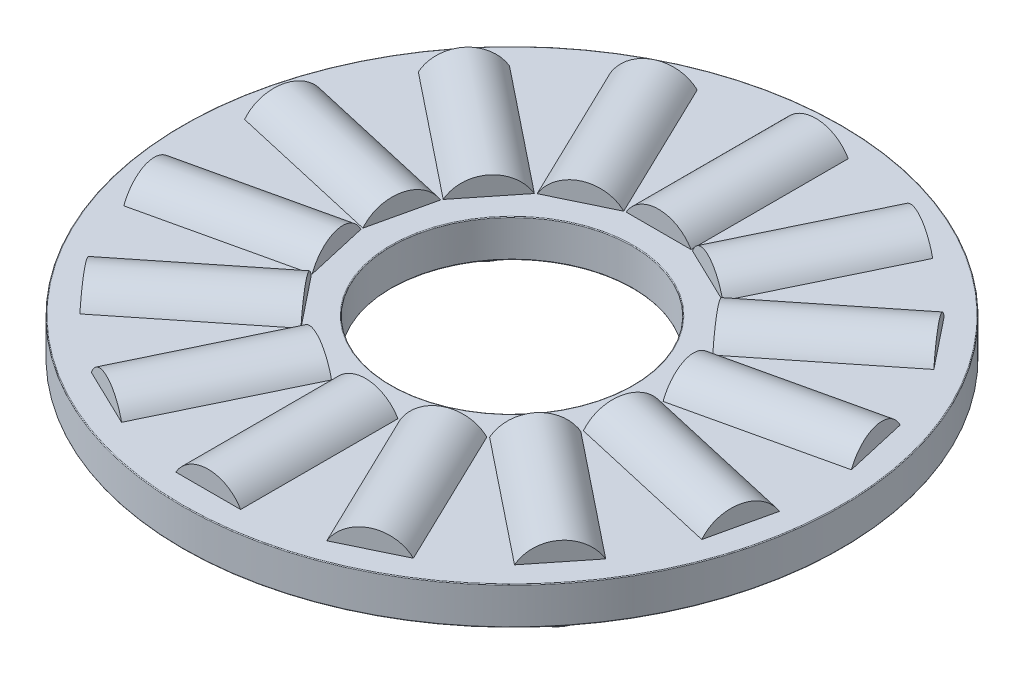
SolidWorks part; units mm, degrees
ref_plane "Front Plane" through (0, 0, 0) normal (0, 0, 1) x (1, 0, 0)
ref_plane "Top Plane" through (0, 0, 0) normal (0, 1, 0) x (1, 0, 0)
ref_plane "Right Plane" through (0, 0, 0) normal (1, 0, 0) x (0, 0, -1)
sketch "Sketch1" plane through (0, 0, 0) normal (1, 0, 0) x (0, 0, -1)
  line L0 (-8.7312, 0) -> (8.7312, 0) construction
  line L1 (0, -0.9922) -> (0, 0.9922) construction
  line L2 (-8.7312, 0.4961) -> (-3.2004, 0.4961)
  line L3 (-8.7312, 0.4961) -> (-8.7312, -0.4961)
  line L4 (-8.7312, -0.4961) -> (-3.2004, -0.4961)
  line L5 (-3.2004, 0.4961) -> (-3.2004, -0.4961)
  line L7 (-5.9658, 0.9922) -> (-5.9658, 0.4961) construction
  line L8 (-8.0494, 0.9922) -> (-3.8822, 0.9922) construction
  line L9 (-8.0494, 0.9922) -> (-8.0494, -0.9922) construction
  line L10 (-8.0494, -0.9922) -> (-3.8822, -0.9922) construction
  line L11 (-3.8822, 0.9922) -> (-3.8822, -0.9922) construction
  point P16 (-8.0494, 0)
  dimension "D1" = 4.1672
  dimension "OD" = 17.4625
  dimension "Shaft Dia" = 6.4008
  dimension "Th" = 1.9844
  dimension "D2" = 0.9922
  dimension "D3" = 5.5308
revolve "Revolve1" add sketch "Sketch1" angle 360 about L1
sketch "Sketch3" plane through (0, 0, 0) normal (1, 0, 0) x (0, 0, -1)
  line L0 (-8.0494, 0.9922) -> (-8.0494, -0.9922) construction
  line L1 (-8.0494, 0) -> (-3.8822, 0)
  line L2 (-8.0494, 0) -> (-8.0494, 0.9922)
  line L3 (-8.0494, 0.9922) -> (-3.8822, 0.9922)
  line L4 (-3.8822, 0) -> (-3.8822, 0.9922)
revolve "Cut-Revolve1" cut sketch "Sketch3" angle 360 about L1
sketch "Sketch2" plane through (0, 0, 0) normal (1, 0, 0) x (0, 0, -1)
  line L1 (-8.0494, 0) -> (-3.8822, 0)
  line L2 (-8.0494, 0) -> (-8.0494, 0.9922)
  line L3 (-8.0494, 0.9922) -> (-3.8822, 0.9922)
  line L4 (-3.8822, 0) -> (-3.8822, 0.9922)
revolve "Revolve2" add sketch "Sketch2" angle 360 about L1
ref_axis "Axis1" through (0, 0.9922, 0) along (0, -1, 0)
pattern_circular "CirPattern1" count 14 every 25.714 about axis through (0, 0.9922, 0) along (0, -1, 0) of bodies 187 411
pattern_circular "CirPattern2" count 14 every 25.714 about axis through (0, 0, 0) along (0, 1, 0) of "Cut-Revolve1"
sketch "Sketch4" plane through (0, 0, 0) normal (1, 0, 0) x (0, 0, -1)
  line L0 (-8.7312, 0.4961) -> (-8.7312, -0.4961) construction
  line L1 (-11.9062, 9.1091) -> (-6.35, 9.1091)
  line L2 (-11.9062, 9.1091) -> (-11.9062, 9.9219)
  line L3 (-11.9062, 9.9219) -> (-6.35, 9.9219)
  line L4 (-6.35, 9.1091) -> (-6.35, 9.9219)
  line L5 (-11.9062, -9.9219) -> (-3.2004, -9.9219)
  line L6 (-11.9062, -9.9219) -> (-11.9062, -9.1091)
  line L7 (-11.9062, -9.1091) -> (-3.2004, -9.1091)
  line L8 (-3.2004, -9.9219) -> (-3.2004, -9.1091)
  line L10 (-3.2004, 0.4961) -> (-3.2004, -0.4961) construction
  line L11 (0, 0) -> (-8.7312, 0) construction
  line L12 (-8.7312, 0) -> (8.7312, 0) construction
  line L13 (0, -0.9922) -> (0, 0.9922) construction
  dimension "Ht" = 19.8438
  dimension "Washer Th" = 0.8128
  dimension "Washer ID" = 12.7
  dimension "Washer OD" = 23.8125
fillet "Fillet2" radius 0.0198 4 edges at (0, -0.4961, -3.2004) (0, 0.4961, -3.2004) (0, -0.4961, -8.7312) (0, 0.4961, -8.7312)
equation "\"D2@Sketch1\"= \"Th@Sketch1\" * .5"
equation "\"Rollers@CirPattern1\"= \"OD@Sketch1\" * 20"
equation "\"Angle@CirPattern1\" = 360/\"Rollers@CirPattern1\""
equation "\"D1@CirPattern2\" = \"Rollers@CirPattern1\""
equation "\"D2@CirPattern2\" = \"Angle@CirPattern1\""
equation "\"Ht@Sketch4\" = \"Th@Sketch1\"*10"
